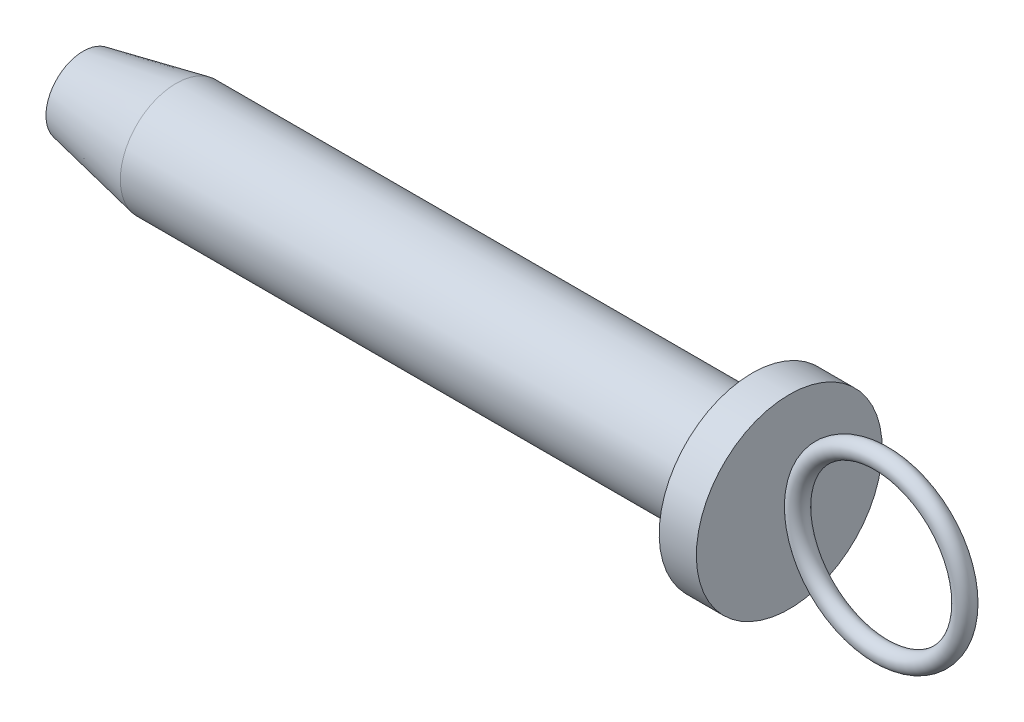
SolidWorks part; units mm, degrees
ref_plane "前视基准面" through (0, 0, 0) normal (0, 0, 1) x (1, 0, 0)
ref_plane "上视基准面" through (0, 0, 0) normal (0, 1, 0) x (1, 0, 0)
ref_plane "右视基准面" through (0, 0, 0) normal (1, 0, 0) x (0, 0, -1)
sketch "草图1" plane through (0, 0, 0) normal (0, 0, 1) x (1, 0, 0)
  line L0 (0, 0) -> (-380, 0)
  line L1 (0, 0) -> (0, 50)
  line L2 (0, 50) -> (-20, 50)
  line L3 (-20, 50) -> (-20, 30)
  line L4 (-20, 30) -> (-330, 30)
  line L5 (-330, 30) -> (-380, 20)
  line L6 (-380, 20) -> (-380, 0)
  dimension "D1" = 50
  dimension "D2" = 20
  dimension "D3" = 310
  dimension "D4" = 30
  dimension "D5" = 50
  dimension "D6" = 20
revolve "旋转1" add sketch "草图1" angle 360 about L0
sketch "草图2" plane through (0, 0, 0) normal (0, 1, 0) x (1, 0, 0)
  line L0 (-1000, 0) -> (49000, 0) construction
  line L2 (49.5, -1000) -> (49.5, 49000) construction
  line L3 (0, -50) -> (0, 50) construction
  circle A0 centre (4.5, 0) radius 5
  dimension "D1" = 10
  dimension "D2" = 45
  dimension "D3" = 4.5
revolve "旋转2" add sketch "草图2" angle 360 about L2
